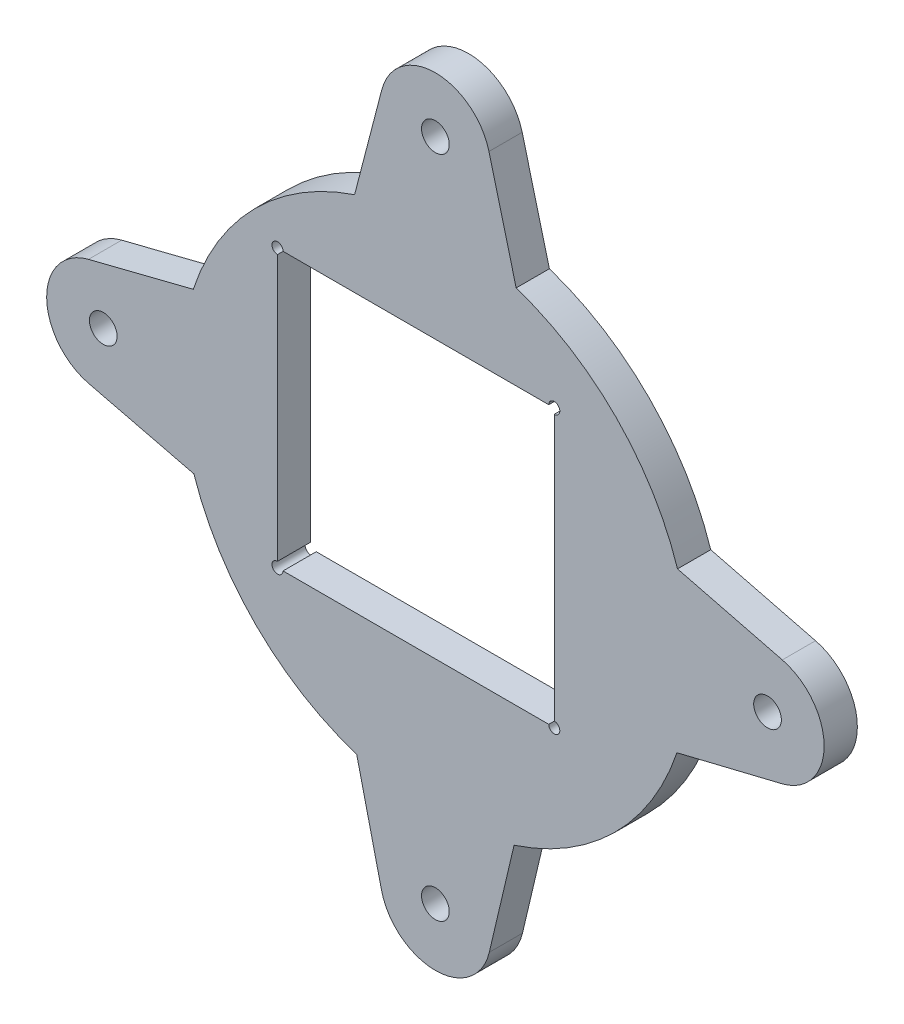
SolidWorks part; units mm, degrees
material "ABS PC"
ref_plane "Front Plane" through (0, 0, 0) normal (0, 0, 1) x (1, 0, 0)
ref_plane "Top Plane" through (0, 0, 0) normal (0, 1, 0) x (1, 0, 0)
ref_plane "Right Plane" through (0, 0, 0) normal (1, 0, 0) x (0, 0, -1)
sketch "Sketch1" plane through (0, 0, 0) normal (0, 0, 1) x (1, 0, 0)
  line L0 (-1.851, -4.2566) -> (-1.851, 25.7434) construction
  line L1 (-33.1868, 0.4779) -> (-23.7211, 2.8636)
  line L2 (-16.1131, -15.1084) -> (8.8869, -15.1084)
  line L3 (-16.1131, -15.1084) -> (-16.1131, 9.8916)
  line L4 (-16.1131, 9.8916) -> (8.8869, 9.8916)
  line L5 (8.8869, -15.1084) -> (8.8869, 9.8916)
  line L6 (-16.1131, -15.1084) -> (8.8869, 9.8916) construction
  line L7 (-16.1131, 9.8916) -> (8.8869, -15.1084) construction
  line L8 (-33.1501, -9.228) -> (-23.6667, -11.5421)
  line L9 (-6.7175, -35.6321) -> (-8.9582, -26.131)
  line L10 (3.0155, -35.6321) -> (5.2562, -26.131)
  line L11 (29.4481, -9.228) -> (19.9646, -11.5421)
  line L12 (29.4848, 0.4779) -> (20.0191, 2.8636)
  line L13 (-6.6899, 27.0024) -> (-9.1479, 17.5552)
  line L14 (2.9879, 27.0024) -> (5.4459, 17.5552)
  circle A0 centre (-1.851, 25.7434) radius 1.25
  circle A1 centre (28.149, -4.2566) radius 1.25
  circle A2 centre (-1.851, -34.2566) radius 1.25
  circle A3 centre (-31.851, -4.2566) radius 1.25
  circle A4 centre (-1.851, 25.7434) radius 5 construction
  circle A5 centre (-1.851, -4.2566) radius 23 construction
  circle A6 centre (28.2629, -4.3705) radius 5 construction
  circle A7 centre (-1.851, -34.4844) radius 5 construction
  circle A8 centre (-31.9649, -4.3705) radius 5 construction
  arc A9 (-6.6899, 27.0024) -> (2.9879, 27.0024) centre (-1.851, 25.7434) cw
  arc A10 (29.4848, 0.4779) -> (29.4481, -9.228) centre (28.2629, -4.3705) cw
  arc A11 (3.0155, -35.6321) -> (-6.7175, -35.6321) centre (-1.851, -34.4844) cw
  arc A12 (-33.1501, -9.228) -> (-33.1868, 0.4779) centre (-31.9649, -4.3705) cw
  arc A13 (-23.7211, 2.8636) -> (-9.1479, 17.5552) centre (-1.851, -4.2566) cw
  arc A14 (5.4459, 17.5552) -> (20.0191, 2.8636) centre (-1.851, -4.2566) cw
  arc A15 (19.9646, -11.5421) -> (5.2562, -26.131) centre (-1.851, -4.2566) cw
  arc A16 (-8.9582, -26.131) -> (-23.6667, -11.5421) centre (-1.851, -4.2566) cw
  point P25 (-1.851, -4.3705)
  dimension "D5" = 10
  dimension "D6" = 46
  dimension "D7" = 2.5
  dimension "D2" = 30
  dimension "D3" = 25
  dimension "D4" = 4
  dimension "D1" = 4
extrude "Boss-Extrude1" add sketch "Sketch1" along normal blind 3
sketch "Sketch2" plane through (0, 0, 3) normal (0, 0, 1) x (1, 0, 0)
  circle A0 centre (-16.1131, 9.8916) radius 0.5
  circle A1 centre (8.8869, 9.8916) radius 0.5
  circle A2 centre (8.8869, -15.1084) radius 0.5
  circle A3 centre (-16.1131, -15.1084) radius 0.5
  point P12 (8.8869, -15.1084)
  dimension "D1" = 1
extrude "Cut-Extrude1" cut sketch "Sketch2" against normal blind 10
